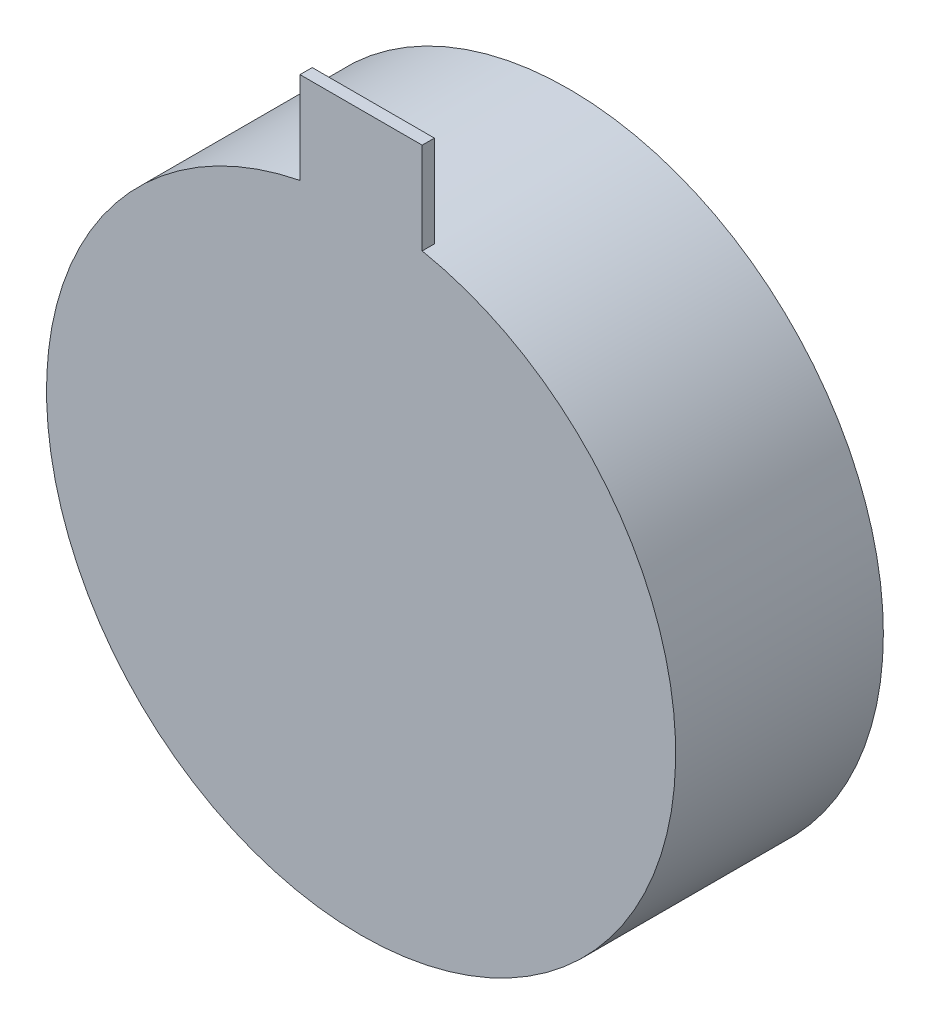
SolidWorks part; units mm, degrees
ref_plane "Plan de face" through (0, 0, 0) normal (0, 0, 1) x (1, 0, 0)
ref_plane "Plan de dessus" through (0, 0, 0) normal (0, 1, 0) x (1, 0, 0)
ref_plane "Plan de droite" through (0, 0, 0) normal (1, 0, 0) x (0, 0, -1)
sketch "Esquisse1" plane through (0, 0, 0) normal (0, 0, 1) x (1, 0, 0)
  circle A0 centre (0, 0) radius 5.15
  dimension "D1" = 10.3
extrude "Boss.-Extru.1" add sketch "Esquisse1" along normal blind 3.4 contours A0
sketch "Esquisse2" plane through (0, 0, 3.4) normal (0, 0, 1) x (1, 0, 0)
  line L0 (1, 5.052) -> (-1, 5.052)
  line L1 (-1, 5.052) -> (-1, 6.552)
  line L2 (-1, 6.552) -> (1, 6.552)
  line L3 (1, 6.552) -> (1, 5.052)
  circle A0 centre (0, 0) radius 5.15 construction
  dimension "D1" = 1.5
  dimension "D2" = 2
extrude "Boss.-Extru.2" add sketch "Esquisse2" against normal blind 0.2 contours L2 L3 L0 L1
